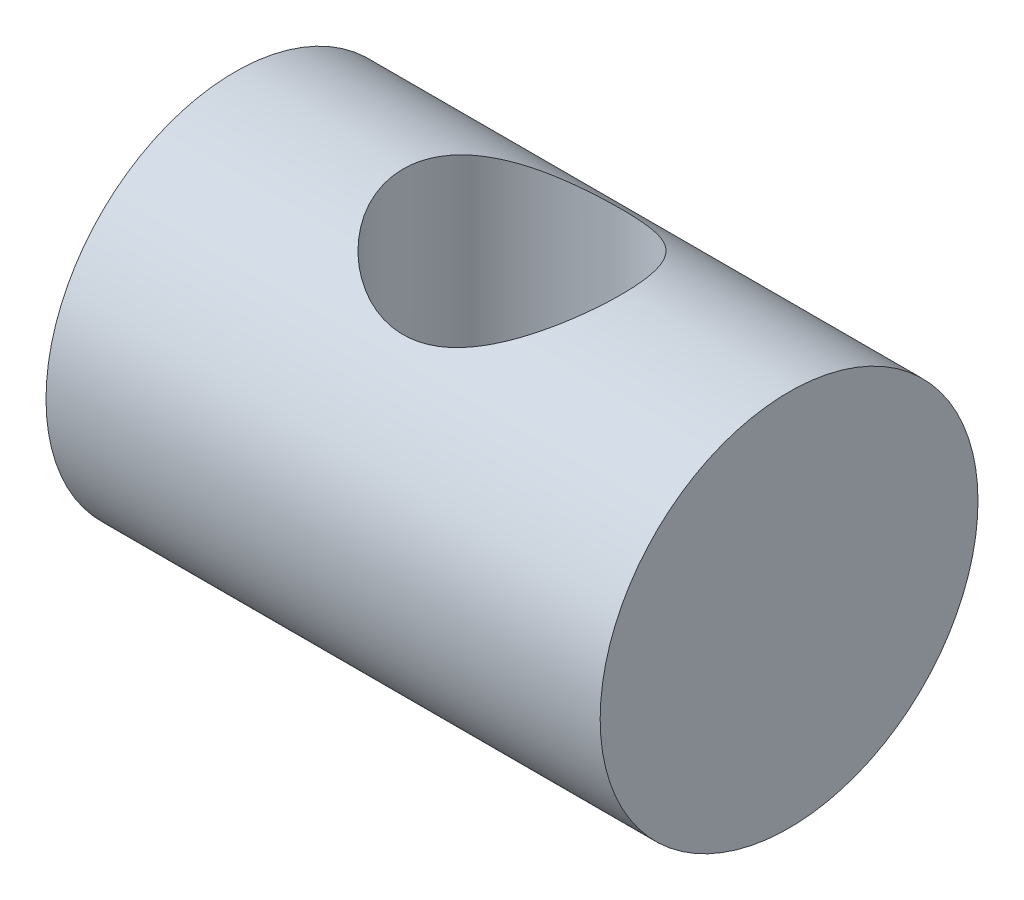
SolidWorks part; units mm, degrees
ref_plane "Front" through (0, 0, 0) normal (0, 0, 1) x (1, 0, 0)
ref_plane "Top" through (0, 0, 0) normal (0, 1, 0) x (1, 0, 0)
ref_plane "Right" through (0, 0, 0) normal (1, 0, 0) x (0, 0, -1)
sketch "Sketch1" plane through (0, 0, 0) normal (1, 0, 0) x (0, 0, -1)
  circle A0 centre (0, 0) radius 7.5
  dimension "D1" = 15
extrude "Boss-Extrude1" add sketch "Sketch1" along normal mid plane 22
sketch "Sketch2" plane through (0, 0, 0) normal (0, 1, 0) x (1, 0, 0)
  circle A0 centre (0, 0) radius 4.325
  dimension "D1" = 8.65
extrude "Cut-Extrude1" cut sketch "Sketch2" along normal through all
